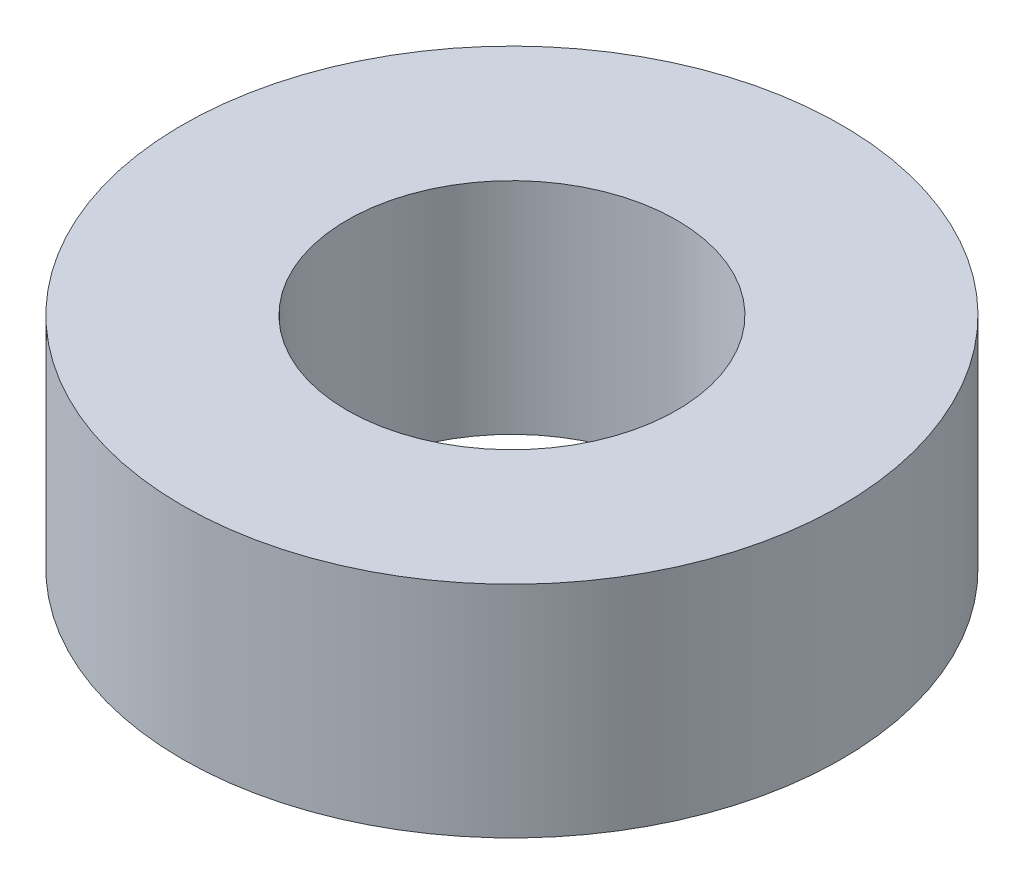
SolidWorks part; units mm, degrees
ref_plane "Front Plane" through (0, 0, 0) normal (0, 0, 1) x (1, 0, 0)
ref_plane "Top Plane" through (0, 0, 0) normal (0, 1, 0) x (1, 0, 0)
ref_plane "Right Plane" through (0, 0, 0) normal (1, 0, 0) x (0, 0, -1)
sketch "Sketch1" plane through (0, 0, 0) normal (0, 1, 0) x (1, 0, 0)
  circle A0 centre (0, 0) radius 2.3813
  circle A1 centre (0, 0) radius 4.7625
  dimension "D1" = 9.525
  dimension "D2" = 4.7625
extrude "Boss-Extrude1" add sketch "Sketch1" along normal blind 3.175
